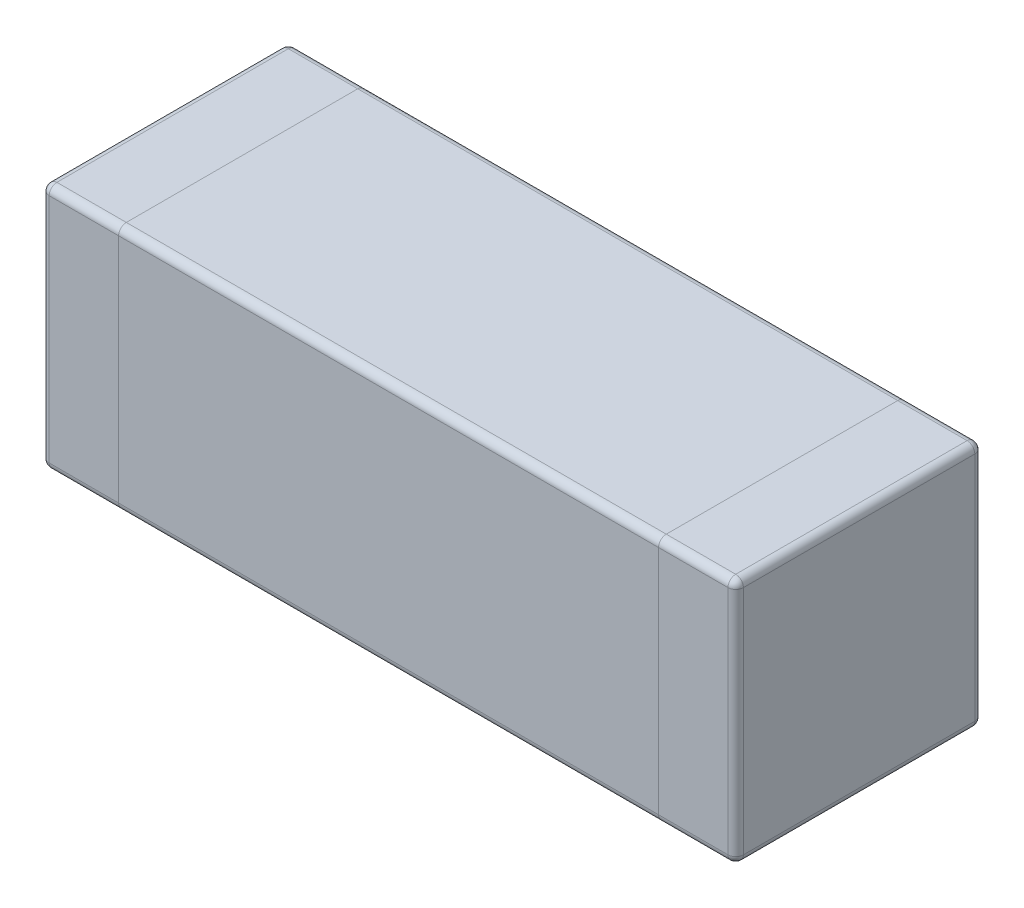
SolidWorks part; units mm, degrees
ref_plane "Front Plane" through (0, 0, 0) normal (0, 0, 1) x (1, 0, 0)
ref_plane "Top Plane" through (0, 0, 0) normal (0, 1, 0) x (1, 0, 0)
ref_plane "Right Plane" through (0, 0, 0) normal (1, 0, 0) x (0, 0, -1)
sketch "Sketch1" plane through (0, 0, 0) normal (0, 1, 0) x (1, 0, 0)
  line L1 (-2.25, -0.8) -> (2.25, -0.8)
  line L2 (-2.25, -0.8) -> (-2.25, 0.8)
  line L3 (-2.25, 0.8) -> (2.25, 0.8)
  line L4 (2.25, -0.8) -> (2.25, 0.8)
  line L5 (-2.25, -0.8) -> (2.25, 0.8) construction
  line L6 (-2.25, 0.8) -> (2.25, -0.8) construction
  point P0 (0, 0)
  dimension "D1" = 4.5
  dimension "D2" = 1.6
extrude "Extrude1" add sketch "Sketch1" along normal blind 1.6
fillet "Fillet1" radius 0.05 12 edges at (2.25, 0.8, -0.8) (-2.25, 0.8, -0.8) (-2.25, 0.8, 0.8) (2.25, 0.8, 0.8) (0, 1.6, 0.8) (-2.25, 1.6, 0) (0, 1.6, -0.8) (2.25, 1.6, 0) (0, 0, -0.8) (-2.25, 0, 0) (0, 0, 0.8) (2.25, 0, 0)
sketch "Sketch2" plane through (0, 0, 0) normal (0, 1, 0) x (1, 0, 0)
  line L0 (-2.2, 0.8) -> (2.2, 0.8) construction
  line L1 (-1.75, -0.8) -> (1.75, -0.8)
  line L2 (-1.75, -0.8) -> (-1.75, 0.8)
  line L3 (-1.75, 0.8) -> (1.75, 0.8)
  line L4 (1.75, -0.8) -> (1.75, 0.8)
  line L5 (2.2, -0.8) -> (-2.2, -0.8) construction
  line L6 (0, 0.75) -> (0, -0.6635) construction
  line L7 (2.2, 0.75) -> (-2.2, 0.75) construction
  line L9 (-2.25, -0.75) -> (-2.25, 0.75) construction
  dimension "D1" = 0.5
split line "Split Line3"
